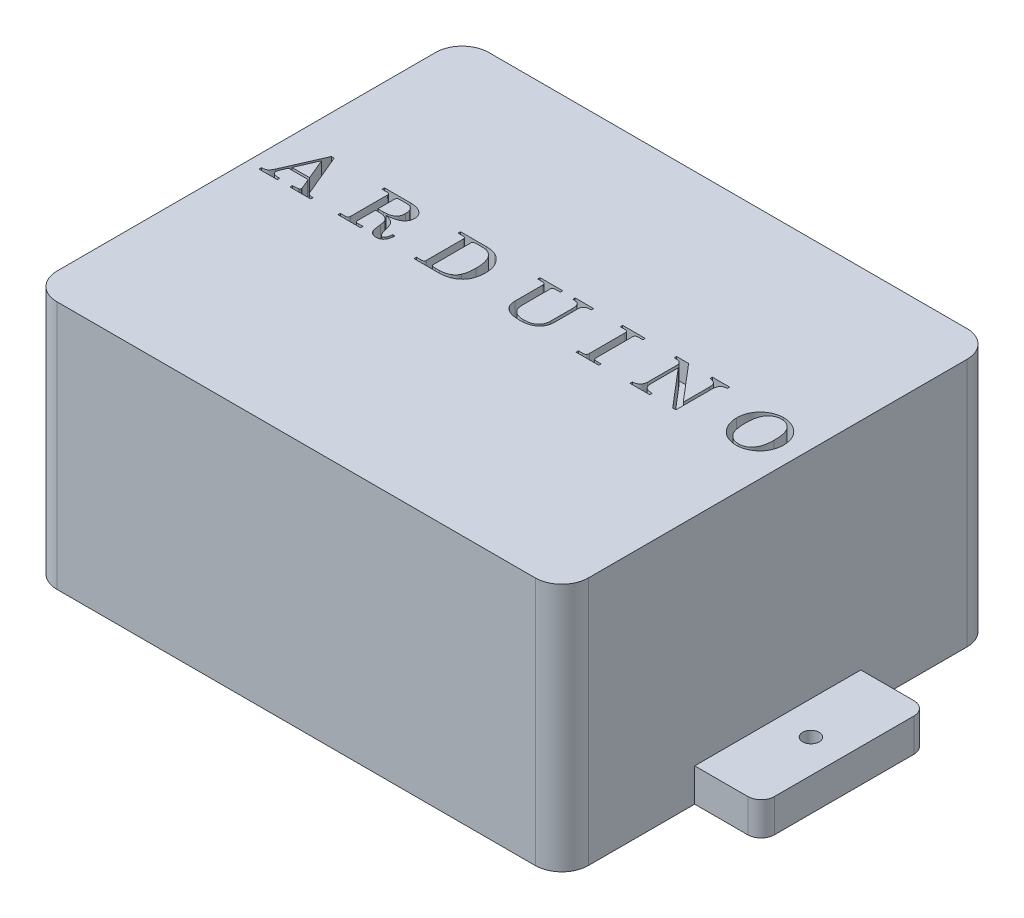
SolidWorks part; units mm, degrees
ref_plane "Front Plane" through (0, 0, 0) normal (0, 0, 1) x (1, 0, 0)
ref_plane "Top Plane" through (0, 0, 0) normal (0, 1, 0) x (1, 0, 0)
ref_plane "Right Plane" through (0, 0, 0) normal (1, 0, 0) x (0, 0, -1)
sketch "Sketch2" plane through (0, 0, 0) normal (0, 1, 0) x (1, 0, 0)
  line L0 (-50.8, 0) -> (50.8, 0) construction
  line L1 (0, -41.275) -> (0, 41.275) construction
  line L3 (-50.8, 41.275) -> (50.8, 41.275)
  line L4 (-50.8, 41.275) -> (-50.8, -41.275)
  line L5 (-50.8, -41.275) -> (50.8, -41.275)
  line L6 (50.8, 41.275) -> (50.8, -41.275)
  point P4 (0, 0)
  point P8 (0, 0)
  point P12 (0, 0)
  dimension "D1" = 82.55
  dimension "D2" = 101.6
  dimension "D3" = 50.8
  dimension "D4" = 41.275
extrude "Boss-Extrude1" add sketch "Sketch2" along normal blind 47.625 contours L4 L5 L6 L3
fillet "Fillet1" radius 5.08 4 edges at (50.8, 23.8125, 41.275) (50.8, 23.8125, -41.275) (-50.8, 23.8125, 41.275) (-50.8, 23.8125, -41.275)
sketch "Sketch3" plane through (0, 0, 0) normal (0, 1, 0) x (1, 0, 0)
  line L0 (50.8, -15.875) -> (63.5, -15.875)
  line L1 (50.8, 36.195) -> (50.8, -36.195) construction
  line L2 (50.8, 15.875) -> (63.5, 15.875)
  line L3 (-45.72, -41.275) -> (45.72, -41.275) construction
  line L4 (-45.72, 41.275) -> (45.72, 41.275) construction
  line L5 (63.5, 15.875) -> (63.5, -15.875)
  line L6 (50.8, 15.875) -> (50.8, -15.875)
  dimension "D1" = 25.4
  dimension "D2" = 25.4
  dimension "D3" = 12.7
sketch "Sketch4" plane through (0, 0, 0) normal (0, 1, 0) x (1, 0, 0)
  line L0 (-50.8, -15.875) -> (-63.5, -15.875)
  line L1 (-50.8, 36.195) -> (-50.8, -36.195) construction
  line L2 (-50.8, 15.875) -> (-63.5, 15.875)
  line L3 (-45.72, 41.275) -> (45.72, 41.275) construction
  line L4 (-45.72, -41.275) -> (45.72, -41.275) construction
  line L5 (-63.5, 15.875) -> (-63.5, -15.875)
  line L6 (-50.8, 15.875) -> (-50.8, -15.875)
  dimension "D1" = 25.4
  dimension "D2" = 25.4
  dimension "D3" = 12.7
extrude "Boss-Extrude2" add sketch "Sketch4" along normal blind 6.35 contours L5 L0 L6 L2
extrude "Boss-Extrude3" add sketch "Sketch3" along normal blind 6.35
fillet "Fillet2" radius 2.54 4 edges at (-63.5, 3.175, 15.875) (-63.5, 3.175, -15.875) (63.5, 3.175, -15.875) (63.5, 3.175, 15.875)
sketch "Sketch5" plane through (0, 0, 0) normal (0, 1, 0) x (1, 0, 0)
  line L0 (15.875, 41.275) -> (15.875, 53.975)
  line L1 (-45.72, 41.275) -> (45.72, 41.275) construction
  line L2 (-15.875, 41.275) -> (-15.875, 53.975)
  line L3 (-50.8, 36.195) -> (-50.8, -36.195) construction
  line L4 (50.8, 36.195) -> (50.8, -36.195) construction
  line L5 (-15.875, 53.975) -> (15.875, 53.975)
  line L6 (-15.875, 41.275) -> (15.875, 41.275)
  dimension "D1" = 34.925
  dimension "D2" = 34.925
  dimension "D3" = 12.7
extrude "Boss-Extrude4" add sketch "Sketch5" along normal blind 6.35 contours L0 L5 L2 L6
fillet "Fillet3" radius 2.54 2 edges at (-15.875, 3.175, -53.975) (15.875, 3.175, -53.975)
sketch "Sketch6" plane through (0, 6.35, 0) normal (0, 1, 0) x (1, 0, 0)
  line L0 (0, 53.975) -> (0, 41.275) construction
  line L1 (-13.335, 53.975) -> (13.335, 53.975) construction
  line L2 (-45.72, 41.275) -> (45.72, 41.275) construction
  line L3 (-15.875, 47.625) -> (15.875, 47.625) construction
  line L4 (15.875, 41.275) -> (15.875, 51.435) construction
  circle A0 centre (0, 47.625) radius 1.5875
  point P11 (0, 47.625)
  dimension "D1" = 3.175
extrude "Cut-Extrude1" cut sketch "Sketch6" against normal blind 9.398
sketch "Sketch7" plane through (0, 6.35, 0) normal (0, 1, 0) x (1, 0, 0)
  line L0 (-63.5, 0) -> (-50.8, 0) construction
  line L1 (-63.5, 13.335) -> (-63.5, -13.335) construction
  line L2 (-50.8, 36.195) -> (-50.8, -36.195) construction
  line L3 (-57.15, -15.875) -> (-57.15, 15.875) construction
  line L4 (-50.8, 15.875) -> (-60.96, 15.875) construction
  circle A0 centre (-57.15, 0) radius 1.5875
  point P11 (-57.15, 0)
  dimension "D1" = 3.175
extrude "Cut-Extrude2" cut sketch "Sketch7" against normal blind 9.398
sketch "Sketch8" plane through (0, 6.35, 0) normal (0, 1, 0) x (1, 0, 0)
  line L0 (63.5, 0) -> (50.8, 0) construction
  line L1 (63.5, -13.335) -> (63.5, 13.335) construction
  line L2 (50.8, 15.875) -> (50.8, -15.875) construction
  line L3 (57.15, -15.875) -> (57.15, 15.875) construction
  line L4 (60.96, 15.875) -> (50.8, 15.875) construction
  circle A0 centre (57.15, 0) radius 1.5875
  point P11 (57.15, 0)
  dimension "D1" = 3.175
extrude "Cut-Extrude3" cut sketch "Sketch8" against normal blind 9.398 contours A0
sketch "Sketch9" plane through (0, 47.625, 0) normal (0, 1, 0) x (1, 0, 0)
  line L0 (-50.8, 0) -> (50.8, 0) construction
  line L1 (50.8, 36.195) -> (50.8, -36.195) construction
  line L2 (0, 41.275) -> (0, -41.275) construction
  line L3 (-45.72, -41.275) -> (45.72, -41.275) construction
  text T0 "ARDUINO" font "Century Schoolbook" height 8.89
  point P6 (0, 0)
  point P12 (0, 0)
extrude "Cut-Extrude4" cut sketch "Sketch9" against normal blind 3.81
